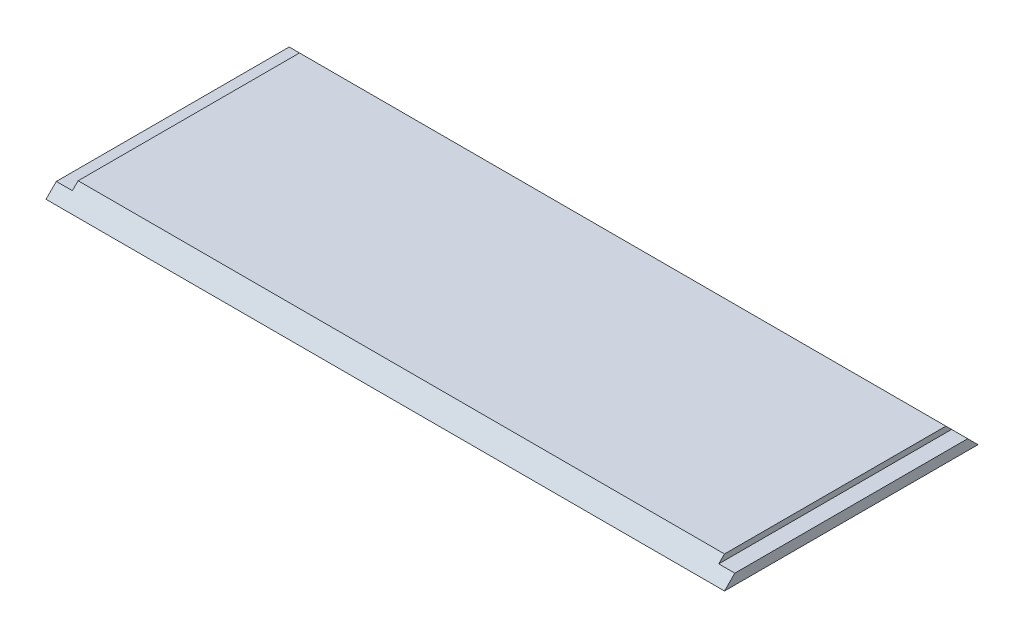
SolidWorks part; units mm, degrees
material "柚木"
ref_plane "前视基准面" through (0, 0, 0) normal (0, 0, 1) x (1, 0, 0)
ref_plane "上视基准面" through (0, 0, 0) normal (0, 1, 0) x (1, 0, 0)
ref_plane "右视基准面" through (0, 0, 0) normal (1, 0, 0) x (0, 0, -1)
sketch "草图1" plane through (0, 0, 0) normal (0, 1, 0) x (1, 0, 0)
  line L1 (-45.1742, 28.0927) -> (73.1258, 28.0927)
  line L2 (-45.1742, 28.0927) -> (-45.1742, -16.1073)
  line L3 (-45.1742, -16.1073) -> (73.1258, -16.1073)
  line L4 (73.1258, 28.0927) -> (73.1258, -16.1073)
  dimension "D1" = 118.3
  dimension "D2" = 44.2
extrude "凸台-拉伸1" add sketch "草图1" along normal blind 2.8
sketch "草图2" plane through (0, 2.8, 0) normal (0, 1, 0) x (1, 0, 0)
  line L0 (-45.1742, -16.1073) -> (73.1258, -16.1073) construction
  line L1 (-45.1742, 28.0927) -> (-42.3742, 28.0927)
  line L2 (-45.1742, 28.0927) -> (-45.1742, -16.1073)
  line L3 (-45.1742, -16.1073) -> (-42.3742, -16.1073)
  line L4 (-42.3742, 28.0927) -> (-42.3742, -16.1073)
  line L6 (73.1258, 28.0927) -> (70.3258, 28.0927)
  line L7 (73.1258, 28.0927) -> (73.1258, -16.1073)
  line L8 (73.1258, -16.1073) -> (70.3258, -16.1073)
  line L9 (70.3258, 28.0927) -> (70.3258, -16.1073)
  dimension "D1" = 2.8
  dimension "D2" = 2.8
extrude "切除-拉伸1" cut sketch "草图2" against normal blind 1
sketch "草图3" plane through (-45.1742, 0, 0) normal (-1, 0, 0) x (0, 0, 1)
  line L0 (-28.0927, 0) -> (-28.0927, 2.8)
  line L1 (-28.0927, 2.8) -> (-25.2927, 2.8)
  line L2 (16.1073, 2.8) -> (-28.0927, 2.8) construction
  line L3 (-25.2927, 2.8) -> (-28.0927, 0)
  line L4 (16.1073, 0) -> (16.1073, 2.8)
  line L5 (16.1073, 2.8) -> (13.3073, 2.8)
  line L6 (13.3073, 2.8) -> (16.1073, 0)
  dimension "D1" = 45
  dimension "D2" = 45
extrude "切除-拉伸2" cut sketch "草图3" against normal through all
